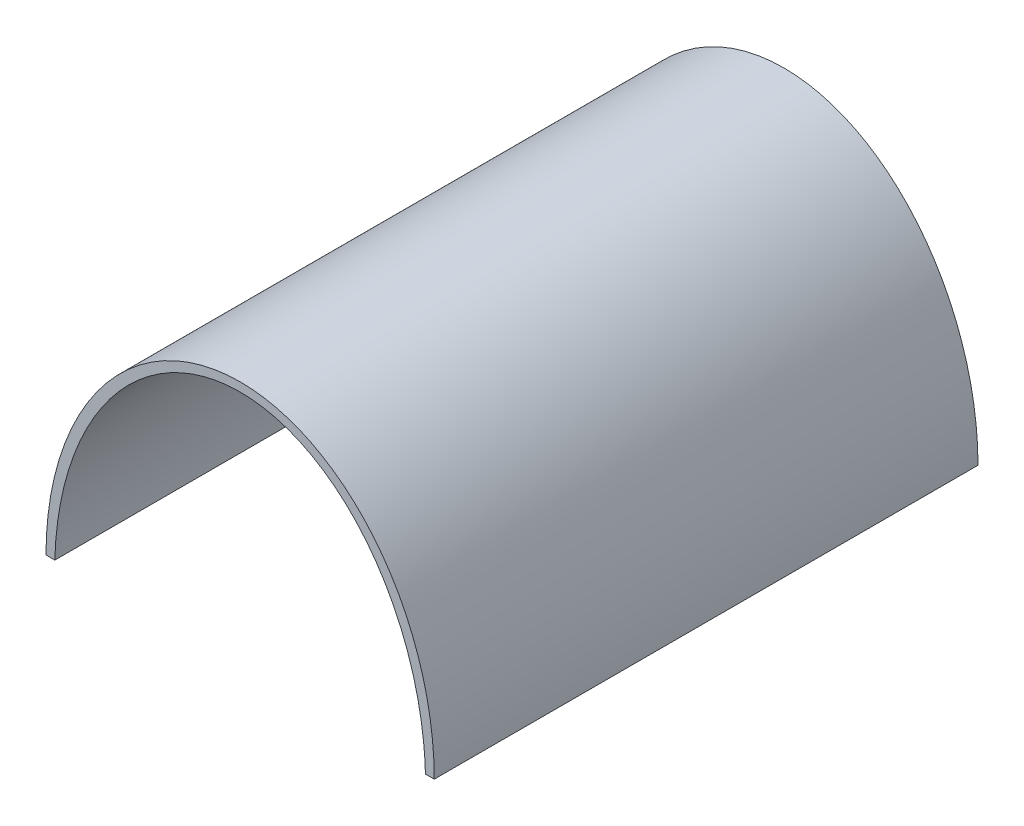
SolidWorks part; units mm, degrees
material "Glass"
ref_plane "Front Plane" through (0, 0, 0) normal (0, 0, 1) x (1, 0, 0)
ref_plane "Top Plane" through (0, 0, 0) normal (0, 1, 0) x (1, 0, 0)
ref_plane "Right Plane" through (0, 0, 0) normal (1, 0, 0) x (0, 0, -1)
sketch "Sketch1" plane through (0, 0, 0) normal (0, 0, 1) x (1, 0, 0)
  line L0 (-419.1, 0) -> (-400.05, 0)
  line L1 (419.1, 0) -> (400.05, 0)
  ellipse E0 centre (0, 0) end of major axis (0, -533.4) minor radius 419.1 (419.1, 0) -> (-419.1, 0) ccw
  ellipse E1 centre (0, -19.05) end of major axis (0, -552.45) minor radius 400.3054 (400.05, 0) -> (-400.05, 0) ccw
  dimension "D1" = 838.2
  dimension "D2" = 1066.8
  dimension "D3" = 19.05
  dimension "D4" = 19.05
  dimension "D5" = 19.05
extrude "Boss-Extrude2" add sketch "Sketch1" along normal blind 990.6 and the other way up to surface (183.2559 mm away)
